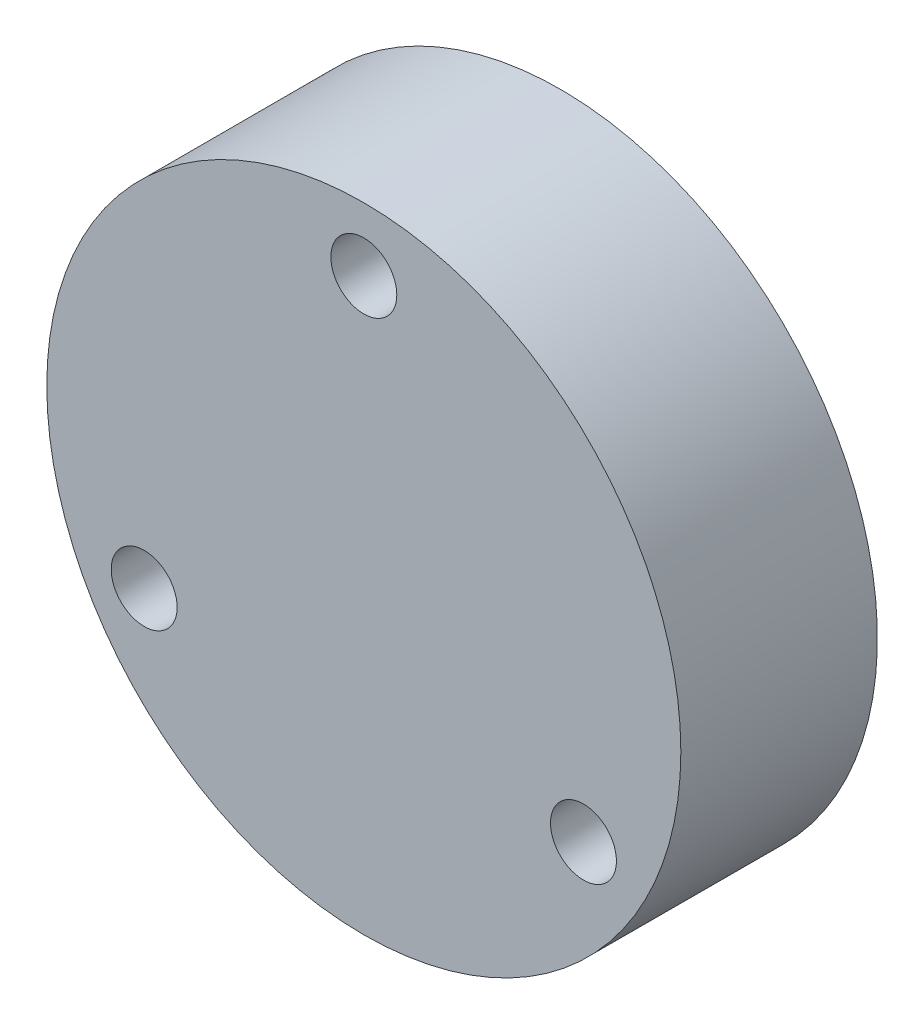
SolidWorks part; units mm, degrees
material "5052-H34"
ref_plane "正面" through (0, 0, 0) normal (0, 0, 1) x (1, 0, 0)
ref_plane "平面" through (0, 0, 0) normal (0, 1, 0) x (1, 0, 0)
ref_plane "右側面" through (0, 0, 0) normal (1, 0, 0) x (0, 0, -1)
sketch "ｽｹｯﾁ1" plane through (0, 0, 0) normal (0, 0, 1) x (1, 0, 0)
  circle A0 centre (0, 0) radius 12.5
  dimension "D1" = 25
extrude "ﾎﾞｽ - 押し出し1" add sketch "ｽｹｯﾁ1" along normal blind 12
sketch "ｽｹｯﾁ2" plane through (0, 0, 12) normal (0, 0, 1) x (1, 0, 0)
  circle A1 centre (0, 0) radius 10 construction
  circle A2 centre (0, 10) radius 1.3
  circle A3 centre (8.6603, -5) radius 1.3
  circle A4 centre (-8.6603, -5) radius 1.3
  dimension "D2" = 20
  dimension "D3" = 2.6
  dimension "D4" = 3
extrude "ｶｯﾄ - 押し出し1" cut sketch "ｽｹｯﾁ2" against normal through all
sketch "ｽｹｯﾁ3" plane through (0, 0, 0) normal (0, 0, -1) x (-1, 0, 0)
  circle A0 centre (0, 0) radius 5
  circle A2 centre (0, 0) radius 12.5
  circle A3 centre (0, 0) radius 12.5
  dimension "D1" = 10
  dimension "D2" = 0
extrude "ｶｯﾄ - 押し出し2" cut sketch "ｽｹｯﾁ3" against normal blind 4.25
sketch "ｽｹｯﾁ4" plane through (0, 0, 4.25) normal (0, 0, -1) x (-1, 0, 0)
  circle A0 centre (0, 0) radius 6
  circle A1 centre (0, 0) radius 5
  circle A2 centre (0, 0) radius 5
  dimension "D5" = 12
  dimension "D1" = 0
extrude "ﾎﾞｽ - 押し出し2" add sketch "ｽｹｯﾁ4" along normal blind 1
